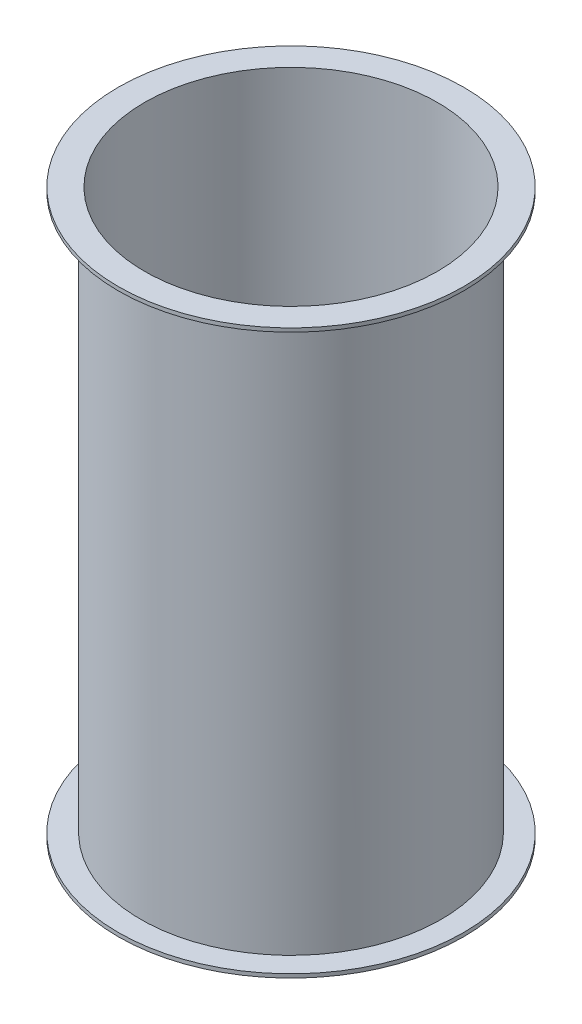
SolidWorks part; units mm, degrees
material "AISI 304"
ref_plane "Piano frontale" through (0, 0, 0) normal (0, 0, 1) x (1, 0, 0)
ref_plane "Piano superiore" through (0, 0, 0) normal (0, 1, 0) x (1, 0, 0)
ref_plane "Piano destro" through (0, 0, 0) normal (1, 0, 0) x (0, 0, -1)
sketch "Schizzo1" plane through (0, 0, 0) normal (0, 1, 0) x (1, 0, 0)
  circle A0 centre (0, 0) radius 40
extrude "Estrusione-Sottile1" add sketch "Schizzo1" along normal blind 150 thin thin type one direction reverse wall 1
sketch "Schizzo2" plane through (0, 150, 0) normal (0, 1, 0) x (1, 0, 0)
  circle A0 centre (0, 0) radius 40 construction
  circle A1 centre (0, 0) radius 40
  circle A2 centre (0, 0) radius 46
  dimension "D1" = 6
extrude "Estrusione-Estrusione1" add sketch "Schizzo2" against normal blind 1
sketch "Schizzo3" plane through (0, 0, 0) normal (0, -1, 0) x (1, 0, 0)
  circle A0 centre (0, 0) radius 40 construction
  circle A1 centre (0, 0) radius 40
  circle A2 centre (0, 0) radius 46
  dimension "D1" = 6
extrude "Estrusione-Estrusione2" add sketch "Schizzo3" against normal blind 1
sketch "Schizzo4" plane through (0, 0, 0) normal (0, -1, 0) x (1, 0, 0)
  circle A0 centre (0, 0) radius 42 construction
